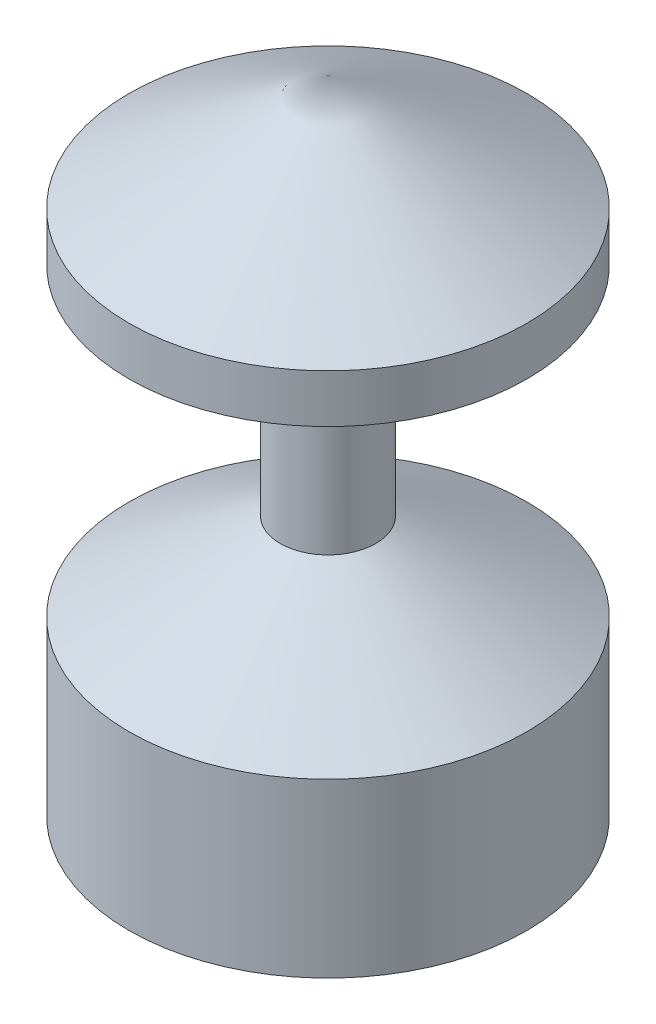
SolidWorks part; units mm, degrees
ref_plane "Front Plane" through (0, 0, 0) normal (0, 0, 1) x (1, 0, 0)
ref_plane "Top Plane" through (0, 0, 0) normal (0, 1, 0) x (1, 0, 0)
ref_plane "Right Plane" through (0, 0, 0) normal (1, 0, 0) x (0, 0, -1)
sketch "Sketch1" plane through (0, 0, 0) normal (1, 0, 0) x (0, 0, -1)
  line L0 (0, 5.4848) -> (-9.5, 0)
  line L1 (-12.5, -1) -> (-9.5, -1)
  line L2 (-12.5, -1) -> (-12.5, 9.815)
  line L3 (-12.5, 9.815) -> (-3, 15.2998)
  line L4 (-3, 15.2998) -> (-3, 29)
  line L5 (-3, 29) -> (-12.5, 29)
  line L6 (-12.5, 29) -> (-12.5, 32.0331)
  line L7 (-12.5, 32.0331) -> (0, 39.25)
  line L8 (0, 39.25) -> (0, 5.4848)
  line L9 (0, 5.4848) -> (0, 0) construction
  line L10 (0, 0) -> (-9.5, 0) construction
  line L11 (-9.5, -1) -> (-9.5, 0)
  dimension "D1" = 30
  dimension "D2" = 12.5
  dimension "D3" = 40.25
  dimension "D4" = 30
  dimension "D5" = 6
  dimension "D6" = 1
  dimension "D7" = 3
  dimension "D8" = 10
revolve "Revolve1" add sketch "Sketch1" angle 360 about L8
